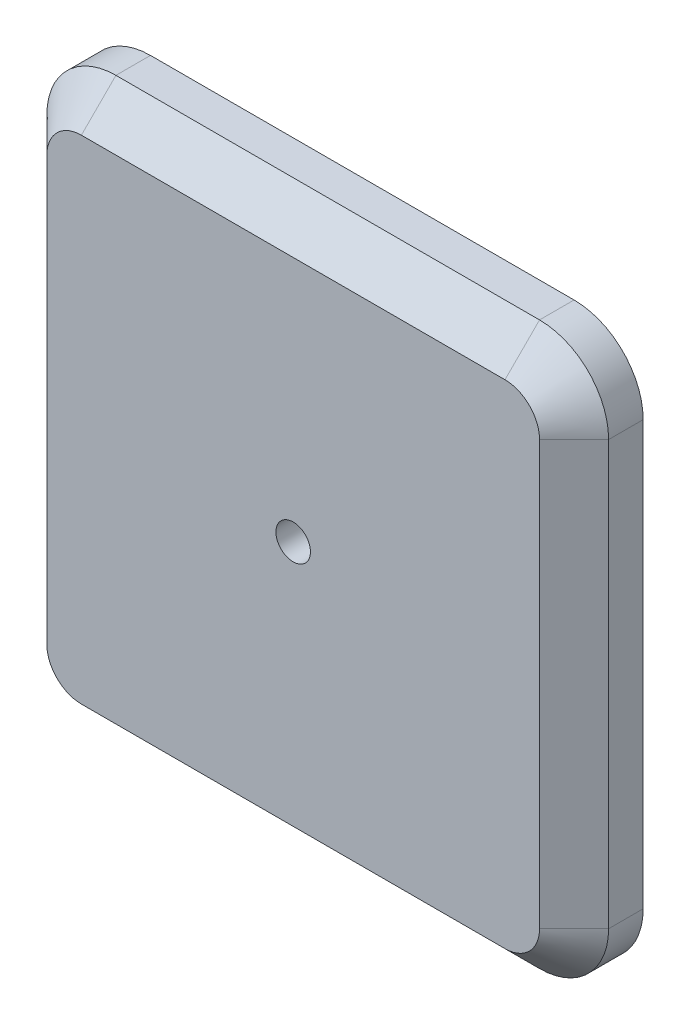
SolidWorks part; units mm, degrees
ref_plane "Front Plane" through (0, 0, 0) normal (0, 0, 1) x (1, 0, 0)
ref_plane "Top Plane" through (0, 0, 0) normal (0, 1, 0) x (1, 0, 0)
ref_plane "Right Plane" through (0, 0, 0) normal (1, 0, 0) x (0, 0, -1)
sketch "Sketch1" plane through (0, 0, 0) normal (0, 0, 1) x (1, 0, 0)
  line L1 (16.2635, -16.2635) -> (-16.2635, -16.2635)
  line L2 (16.2635, -16.2635) -> (16.2635, 16.2635)
  line L3 (16.2635, 16.2635) -> (-16.2635, 16.2635)
  line L4 (-16.2635, -16.2635) -> (-16.2635, 16.2635)
  line L5 (16.2635, -16.2635) -> (-16.2635, 16.2635) construction
  line L6 (16.2635, 16.2635) -> (-16.2635, -16.2635) construction
  point P0 (0, 0)
  dimension "D1" = 46
extrude "Boss-Extrude1" add sketch "Sketch1" along normal blind 4
fillet "Fillet1" radius 4 4 edges at (-16.2635, -16.2635, 2) (16.2635, -16.2635, 2) (16.2635, 16.2635, 2) (-16.2635, 16.2635, 2)
chamfer "Chamfer1" distance 2 angle 45 8 edges at (0, -16.2635, 4) (15.0919, -15.0919, 4) (-15.0919, -15.0919, 4) (16.2635, 0, 4) (-16.2635, 0, 4) (15.0919, 15.0919, 4) (-15.0919, 15.0919, 4) (0, 16.2635, 4)
sketch "Sketch2" plane through (0, 0, 4) normal (0, 0, 1) x (1, 0, 0)
  circle A0 centre (0, 0) radius 1
  dimension "D1" = 2
extrude "Cut-Extrude1" cut sketch "Sketch2" against normal through all
